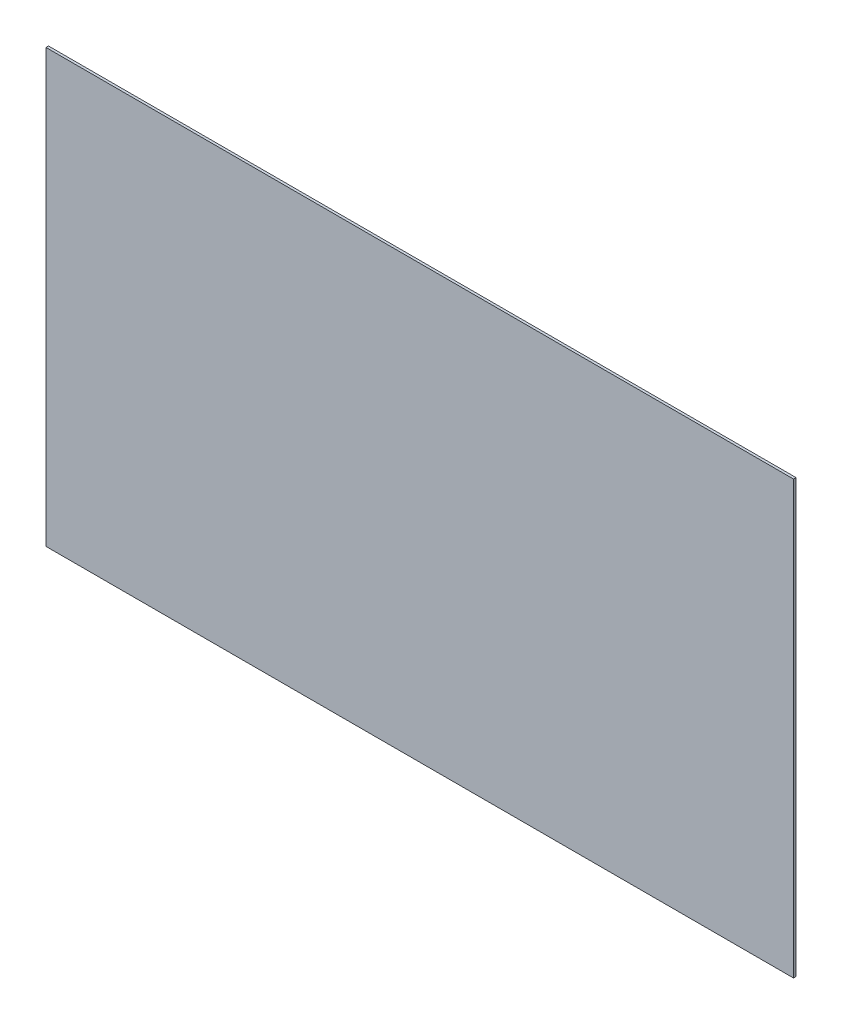
SolidWorks part; units mm, degrees
ref_plane "Front Plane" through (0, 0, 0) normal (0, 0, 1) x (1, 0, 0)
ref_plane "Top Plane" through (0, 0, 0) normal (0, 1, 0) x (1, 0, 0)
ref_plane "Right Plane" through (0, 0, 0) normal (1, 0, 0) x (0, 0, -1)
sketch "Sketch1" plane through (0, 0, 0) normal (0, 0, 1) x (1, 0, 0)
  line L1 (-148.49, -85.85) -> (148.49, -85.85)
  line L2 (-148.49, -85.85) -> (-148.49, 85.85)
  line L3 (-148.49, 85.85) -> (148.49, 85.85)
  line L4 (148.49, -85.85) -> (148.49, 85.85)
  line L5 (-148.49, -85.85) -> (148.49, 85.85) construction
  line L6 (-148.49, 85.85) -> (148.49, -85.85) construction
  point P0 (0, 0)
  dimension "D1" = 171.7
  dimension "D2" = 296.98
extrude "Boss-Extrude1" add sketch "Sketch1" along normal blind 1
